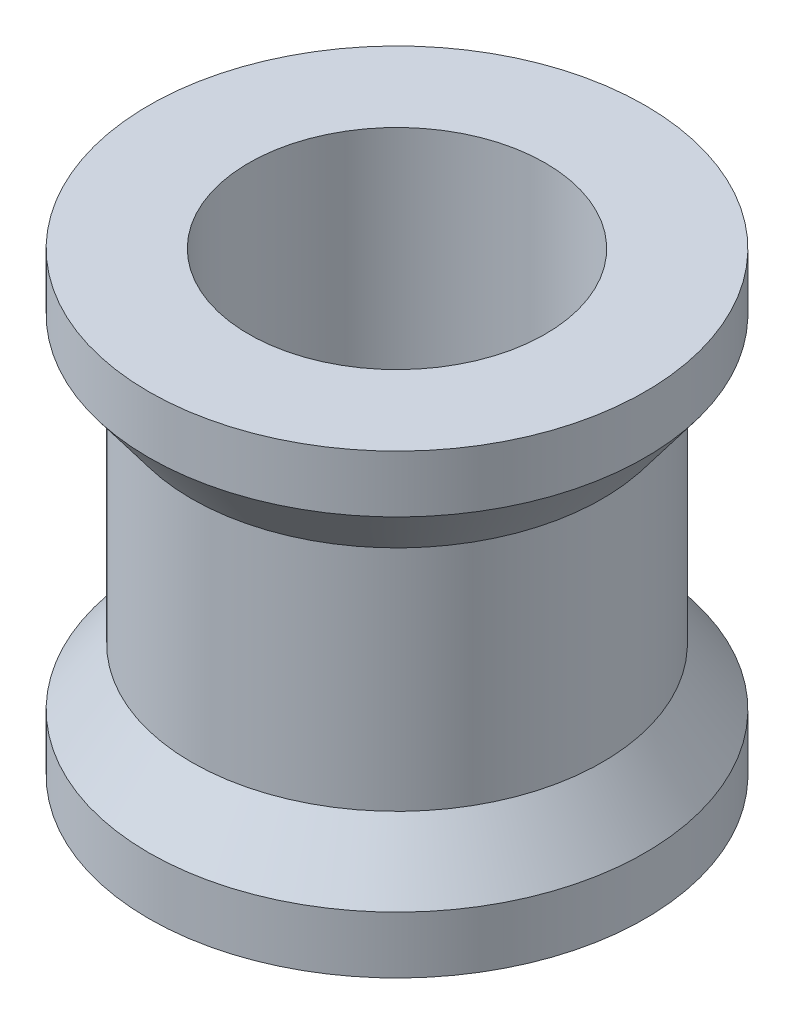
SolidWorks part; units mm, degrees
ref_plane "Front Plane" through (0, 0, 0) normal (0, 0, 1) x (1, 0, 0)
ref_plane "Top Plane" through (0, 0, 0) normal (0, 1, 0) x (1, 0, 0)
ref_plane "Right Plane" through (0, 0, 0) normal (1, 0, 0) x (0, 0, -1)
sketch "Sketch1" plane through (0, 0, 0) normal (0, 0, 1) x (1, 0, 0)
  line L0 (0, 0) -> (0, 8.5153) construction
  line L1 (-4.5632, 4) -> (1.8663, 4) construction
  line L2 (-2.6, 8) -> (-2.6, 0)
  line L3 (-2.6, 0) -> (-4.35, 0)
  line L4 (-4.35, 0) -> (-4.35, 1)
  line L5 (-4.35, 1) -> (-3.6, 2)
  line L6 (-3.6, 2) -> (-3.6, 6)
  line L7 (-4.35, 7) -> (-3.6, 6)
  line L8 (-4.35, 8) -> (-4.35, 7)
  line L9 (-2.6, 8) -> (-4.35, 8)
  point P12 (-3.6, 4)
  point P15 (-2.6, 4)
  dimension "D1" = 4
  dimension "D2" = 5.2
  dimension "D3" = 1
  dimension "D4" = 1.75
  dimension "D5" = 1
  dimension "D6" = 2
revolve "Revolve1" add sketch "Sketch1" angle 360 about L0
